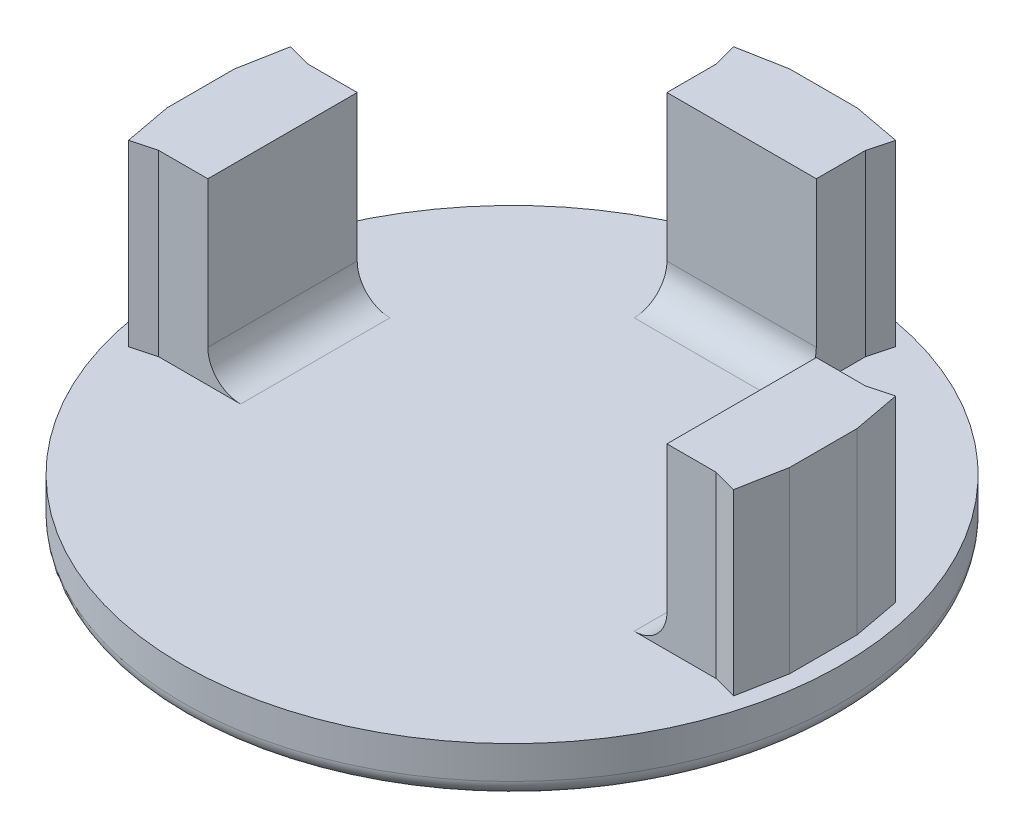
SolidWorks part; units mm, degrees
material "ABS"
ref_plane "Front Plane" through (0, 0, 0) normal (0, 0, 1) x (1, 0, 0)
ref_plane "Top Plane" through (0, 0, 0) normal (0, 1, 0) x (1, 0, 0)
ref_plane "Right Plane" through (0, 0, 0) normal (1, 0, 0) x (0, 0, -1)
sketch "Sketch2" plane through (0, 0, 0) normal (0, 1, 0) x (1, 0, 0)
  circle A0 centre (0, 0) radius 17.6 construction
  circle A1 centre (0, 0) radius 20.1
  dimension "D1" = 35.2
  dimension "D2" = 40.2
extrude "Boss-Extrude2" add sketch "Sketch2" along normal blind 3
sketch "Sketch3" plane through (0, 3, 0) normal (0, 1, 0) x (1, 0, 0)
  line L0 (0, 0) -> (0, 20.1) construction
  line L1 (0, 0) -> (5.2023, 19.4151) construction
  line L2 (0, 0) -> (-5.2023, 19.4151) construction
  line L3 (-4.9434, 18.4492) -> (-4.5552, 17.0003)
  line L4 (4.9434, 18.4492) -> (4.5552, 17.0003)
  line L5 (-4.5552, 17.0003) -> (-4.5552, 14.0003)
  line L6 (-4.5552, 14.0003) -> (4.5552, 14.0003)
  line L7 (4.5552, 14.0003) -> (4.5552, 17.0003)
  line L8 (17.0003, 4.5552) -> (14.0003, 4.5552)
  line L9 (18.4492, 4.9434) -> (17.0003, 4.5552)
  line L10 (18.4492, 4.9434) -> (18.9892, 2.0545)
  line L11 (-4.9434, 18.4492) -> (-2.0545, 18.9892)
  line L12 (-2.0545, 18.9892) -> (2.0545, 18.9892)
  line L13 (2.0545, 18.9892) -> (4.9434, 18.4492)
  line L14 (18.9892, 2.0545) -> (18.9892, -2.0545)
  line L15 (18.9892, -2.0545) -> (18.4492, -4.9434)
  line L16 (18.4492, -4.9434) -> (17.0003, -4.5552)
  line L17 (14.0003, -4.5552) -> (17.0003, -4.5552)
  line L18 (14.0003, 4.5552) -> (14.0003, -4.5552)
  line L19 (4.5552, -17.0003) -> (4.5552, -14.0003) [skipped]
  line L20 (4.9434, -18.4492) -> (4.5552, -17.0003) [skipped]
  line L21 (4.9434, -18.4492) -> (2.0545, -18.9892) [skipped]
  line L22 (2.0545, -18.9892) -> (-2.0545, -18.9892) [skipped]
  line L23 (-2.0545, -18.9892) -> (-4.9434, -18.4492) [skipped]
  line L24 (-4.9434, -18.4492) -> (-4.5552, -17.0003) [skipped]
  line L25 (-4.5552, -14.0003) -> (-4.5552, -17.0003) [skipped]
  line L26 (4.5552, -14.0003) -> (-4.5552, -14.0003) [skipped]
  line L27 (-17.0003, -4.5552) -> (-14.0003, -4.5552)
  line L28 (-18.4492, -4.9434) -> (-17.0003, -4.5552)
  line L29 (-18.4492, -4.9434) -> (-18.9892, -2.0545)
  line L30 (-18.9892, -2.0545) -> (-18.9892, 2.0545)
  line L31 (-18.9892, 2.0545) -> (-18.4492, 4.9434)
  line L32 (-18.4492, 4.9434) -> (-17.0003, 4.5552)
  line L33 (-14.0003, 4.5552) -> (-17.0003, 4.5552)
  line L34 (-14.0003, -4.5552) -> (-14.0003, 4.5552)
  circle A0 centre (0, 0) radius 17.6
  circle A1 centre (0, 0) radius 20.1 construction
  arc A2 (-4.9434, 18.4492) -> (4.9434, 18.4492) centre (0, 0) cw construction
  point P37 (0, 0)
  point P45 (0, 0)
  dimension "D1" = 35.2
  dimension "D5" = 19.1
  dimension "D2" = 30
  dimension "D3" = 15
  dimension "D4" = 20.1
  dimension "D7" = 0.54
  dimension "D6" = 3
  dimension "D8" = 4
extrude "Boss-Extrude4" add sketch "Sketch3" along normal blind 10.9 contours L5 L6 L7 L4 L13 L12 L11 L3 | L28 L27 L34 L33 L32 L31 L30 L29 | L17 L16 L15 L14 L10 L9 L8 L18
fillet "Fillet1" radius 2 3 edges at (14.0003, 3, 0) (0, 3, -14.0003) (-14.0003, 3, 0)
fillet "Fillet2" radius 1 1 edges at (0, 0, 20.1)
ref_plane "Print_bed" through (0, 0, 0) normal (0, -1, 0) x (-1, 0, 0)
equation "\"D2@Sketch2\"=\"D1@Sketch2\"+5"
equation "\"D3@Sketch3\"=\"D2@Sketch3\"/2"
equation "\"D5@Sketch3\"=\"D4@Sketch3\"-1"
